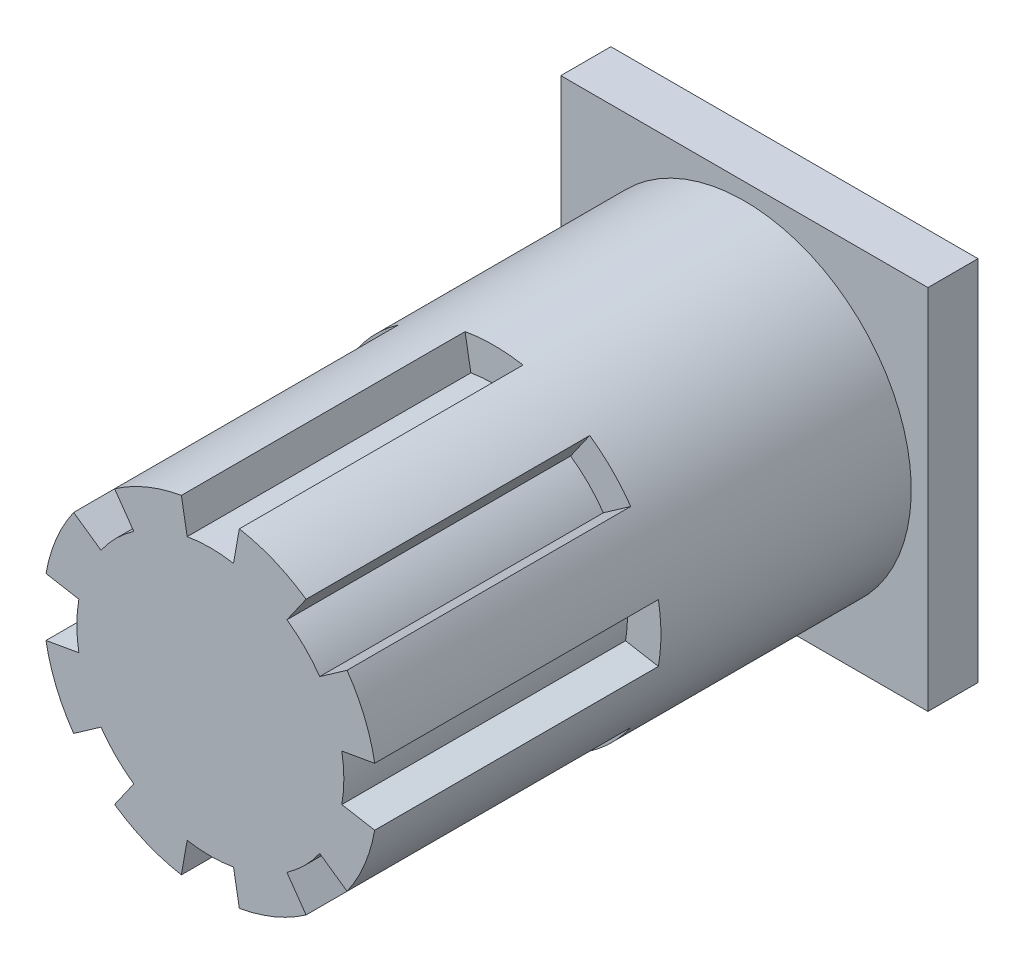
SolidWorks part; units mm, degrees
ref_plane "Front Plane" through (0, 0, 0) normal (0, 0, 1) x (1, 0, 0)
ref_plane "Top Plane" through (0, 0, 0) normal (0, 1, 0) x (1, 0, 0)
ref_plane "Right Plane" through (0, 0, 0) normal (1, 0, 0) x (0, 0, -1)
sketch "Sketch1" plane through (0, 0, 0) normal (0, 0, 1) x (1, 0, 0)
  circle A0 centre (0, 0) radius 10
  dimension "D1" = 20
extrude "Boss-Extrude1" add sketch "Sketch1" along normal blind 20
sketch "Sketch2" plane through (0, 0, 20) normal (0, 0, 1) x (1, 0, 0)
  line L0 (0, 10) -> (0, 0) construction
  line L1 (0, 0) -> (1.7365, 9.8481) construction
  line L2 (0, 0) -> (-1.7365, 9.8481) construction
  line L3 (-1.7365, 9.8481) -> (-1.3892, 7.8785)
  line L4 (1.7365, 9.8481) -> (1.3892, 7.8785)
  circle A0 centre (0, 0) radius 10 construction
  arc A1 (1.3892, 7.8785) -> (-1.3892, 7.8785) centre (0, 0) ccw
  arc A2 (1.7365, 9.8481) -> (-1.7365, 9.8481) centre (0, 0) ccw
  dimension "D2" = 2
  dimension "D1" = 10
extrude "Cut-Extrude1" cut sketch "Sketch2" against normal blind 17
pattern_circular "CirPattern1" count 8 over 360 about axis through (0, 0, 0) along (0, 0, 1) of "Cut-Extrude1"
sketch "Sketch3" plane through (0, 0, 0) normal (0, 0, -1) x (-1, 0, 0)
  circle A0 centre (0, 0) radius 10 construction
  circle A1 centre (0, 0) radius 10
extrude "Boss-Extrude2" add sketch "Sketch3" along normal blind 12
sketch "Sketch4" plane through (0, 0, -12) normal (0, 0, -1) x (-1, 0, 0)
  line L1 (11, 11) -> (-11, 11)
  line L2 (11, 11) -> (11, -11)
  line L3 (11, -11) -> (-11, -11)
  line L4 (-11, 11) -> (-11, -11)
  line L5 (11, 11) -> (-11, -11) construction
  line L6 (11, -11) -> (-11, 11) construction
  point P0 (0, 0)
  dimension "D1" = 22
  dimension "D2" = 22
extrude "Boss-Extrude3" add sketch "Sketch4" along normal blind 3
